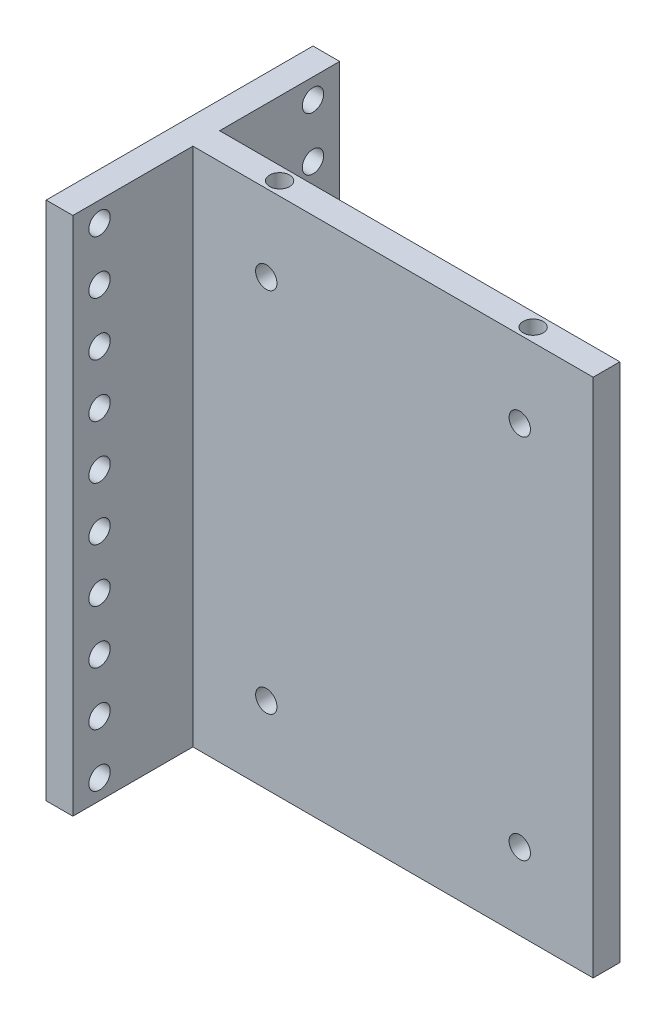
SolidWorks part; units mm, degrees
ref_plane "Front Plane" through (0, 0, 0) normal (0, 0, 1) x (1, 0, 0)
ref_plane "Top Plane" through (0, 0, 0) normal (0, 1, 0) x (1, 0, 0)
ref_plane "Right Plane" through (0, 0, 0) normal (1, 0, 0) x (0, 0, -1)
sketch "Эскиз1" plane through (0, 0, 0) normal (0, 0, 1) x (1, 0, 0)
  line L1 (-19, -27.5) -> (19, -27.5) construction
  line L2 (-19, -27.5) -> (-19, 27.5) construction
  line L3 (-19, 27.5) -> (19, 27.5) construction
  line L4 (19, -27.5) -> (19, 27.5) construction
  line L5 (-19, -27.5) -> (19, 27.5) construction
  line L6 (-19, 27.5) -> (19, -27.5) construction
  line L7 (30, -39) -> (-30, -39)
  line L8 (30, -39) -> (30, 39)
  line L9 (30, 39) -> (-30, 39)
  line L10 (-30, -39) -> (-30, 39)
  line L11 (30, -39) -> (-30, 39) construction
  line L12 (30, 39) -> (-30, -39) construction
  circle A0 centre (-19, 27.5) radius 1.6
  circle A1 centre (19, 27.5) radius 1.6
  circle A2 centre (19, -27.5) radius 1.6
  circle A3 centre (-19, -27.5) radius 1.6
  point P0 (0, 0)
  point P6 (0, 0)
  dimension "D5" = 3.2
  dimension "D1" = 38
  dimension "D2" = 55
  dimension "D3" = 78
  dimension "D4" = 60
extrude "Бобышка-Вытянуть1" add sketch "Эскиз1" along normal blind 4
sketch "Эскиз2" plane through (-30, 0, 0) normal (-1, 0, 0) x (0, 0, 1)
  line L0 (0, 39) -> (4, -39) construction
  line L1 (4, 39) -> (0, 39) construction
  line L2 (0, -39) -> (4, 39) construction
  line L4 (-18, -39) -> (22, -39)
  line L5 (-18, -39) -> (-18, 39)
  line L6 (-18, 39) -> (22, 39)
  line L7 (22, -39) -> (22, 39)
  line L8 (-18, -39) -> (22, 39) construction
  line L9 (-18, 39) -> (22, -39) construction
  line L10 (-14, -36) -> (18, -36) construction
  line L11 (-14, -36) -> (-14, 36) construction
  line L12 (-14, 36) -> (18, 36) construction
  line L13 (18, -36) -> (18, 36) construction
  line L14 (-14, -36) -> (18, 36) construction
  line L15 (-14, 36) -> (18, -36) construction
  circle A0 centre (-14, 36) radius 1.6
  circle A1 centre (18, 36) radius 1.6
  circle A2 centre (18, 28) radius 1.6
  circle A3 centre (18, 20) radius 1.6
  circle A4 centre (18, 12) radius 1.6
  circle A5 centre (18, 4) radius 1.6
  circle A6 centre (18, -4) radius 1.6
  circle A7 centre (18, -12) radius 1.6
  circle A8 centre (18, -20) radius 1.6
  circle A9 centre (18, -28) radius 1.6
  circle A10 centre (18, -36) radius 1.6
  circle A11 centre (-14, 28) radius 1.6
  circle A12 centre (-14, 20) radius 1.6
  circle A13 centre (-14, 12) radius 1.6
  circle A14 centre (-14, 4) radius 1.6
  circle A15 centre (-14, -4) radius 1.6
  circle A16 centre (-14, -12) radius 1.6
  circle A17 centre (-14, -20) radius 1.6
  circle A18 centre (-14, -28) radius 1.6
  circle A19 centre (-14, -36) radius 1.6
  point P8 (2, 0)
  point P13 (2, 0)
  dimension "D4" = 3.2
  dimension "D1" = 40
  dimension "D2" = 72
  dimension "D3" = 32
  dimension "D5" = 2
  dimension "D6" = 10
extrude "Бобышка-Вытянуть2" add sketch "Эскиз2" along normal blind 4
sketch "Эскиз3" plane through (0, -39, 0) normal (0, -1, 0) x (1, 0, 0)
  line L0 (0, 0) -> (0, 4) construction
  line L1 (-30, 0) -> (30, 0) construction
  line L2 (-30, 4) -> (30, 4) construction
  line L3 (-19, 35.5615) -> (-19, -20.9626) construction
  line L4 (19, 35.9834) -> (19, -21.4985) construction
  line L5 (30, 2) -> (-34, 2) construction
  line L6 (30, 4) -> (30, 0) construction
  line L7 (-34, -18) -> (-34, 22) construction
  circle A0 centre (-19, 2) radius 1.5
  circle A1 centre (19, 2) radius 1.5
  dimension "D3" = 3
  dimension "D4" = 3
  dimension "D1" = 19
  dimension "D2" = 19
extrude "Вырез-Вытянуть1" cut sketch "Эскиз3" against normal blind 5
sketch "Эскиз4" plane through (0, 39, 0) normal (0, 1, 0) x (1, 0, 0)
  line L0 (-34, -2) -> (30, -2) construction
  line L1 (-34, -22) -> (-34, 18) construction
  line L2 (30, -4) -> (30, 0) construction
  line L3 (0, 0) -> (0, -4) construction
  line L4 (30, 0) -> (-30, 0) construction
  line L5 (30, -4) -> (-30, -4) construction
  line L6 (-19, 12.4939) -> (-19, -9.2182) construction
  line L7 (19, 7.8987) -> (19, -9.716) construction
  circle A0 centre (-19, -2) radius 1.5
  circle A1 centre (19, -2) radius 1.5
  dimension "D3" = 3
  dimension "D4" = 3
  dimension "D1" = 19
  dimension "D2" = 19
extrude "Вырез-Вытянуть2" cut sketch "Эскиз4" against normal blind 5
